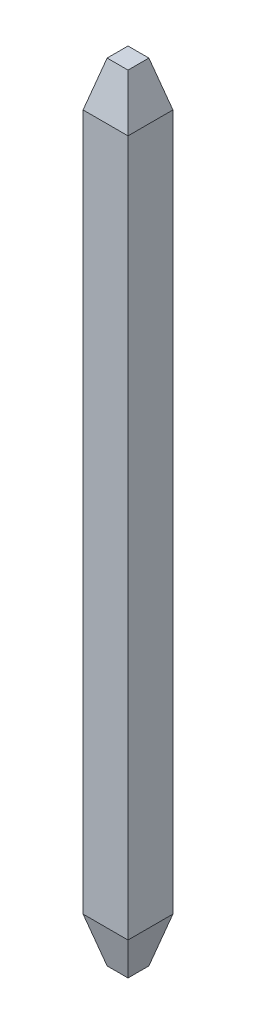
SolidWorks part; units mm, degrees
ref_plane "Front Plane" through (0, 0, 0) normal (0, 0, 1) x (1, 0, 0)
ref_plane "Top Plane" through (0, 0, 0) normal (0, 1, 0) x (1, 0, 0)
ref_plane "Right Plane" through (0, 0, 0) normal (1, 0, 0) x (0, 0, -1)
sketch "Sketch1" plane through (0, 0, 0) normal (0, 1, 0) x (1, 0, 0)
  line L1 (-0.2, -0.2) -> (0.2, -0.2)
  line L2 (-0.2, -0.2) -> (-0.2, 0.2)
  line L3 (-0.2, 0.2) -> (0.2, 0.2)
  line L4 (0.2, -0.2) -> (0.2, 0.2)
  line L5 (-0.2, -0.2) -> (0.2, 0.2) construction
  line L6 (-0.2, 0.2) -> (0.2, -0.2) construction
  point P0 (0, 0)
  dimension "D1" = 0.4
  dimension "D2" = 0.4
extrude "Boss-Extrude1" add sketch "Sketch1" along normal mid plane 7
chamfer "Chamfer2" distance 0.4 angle 15 4 edges at (-0.2, 3.5, 0) (0, 3.5, -0.2) (0.2, 3.5, 0) (0, 3.5, 0.2)
chamfer "Chamfer3" distance 0.4 angle 15 4 edges at (0, -3.5, 0.2) (-0.2, -3.5, 0) (0, -3.5, -0.2) (0.2, -3.5, 0)
equation "\"D2@Sketch1\"=\"D1@Sketch1\""
